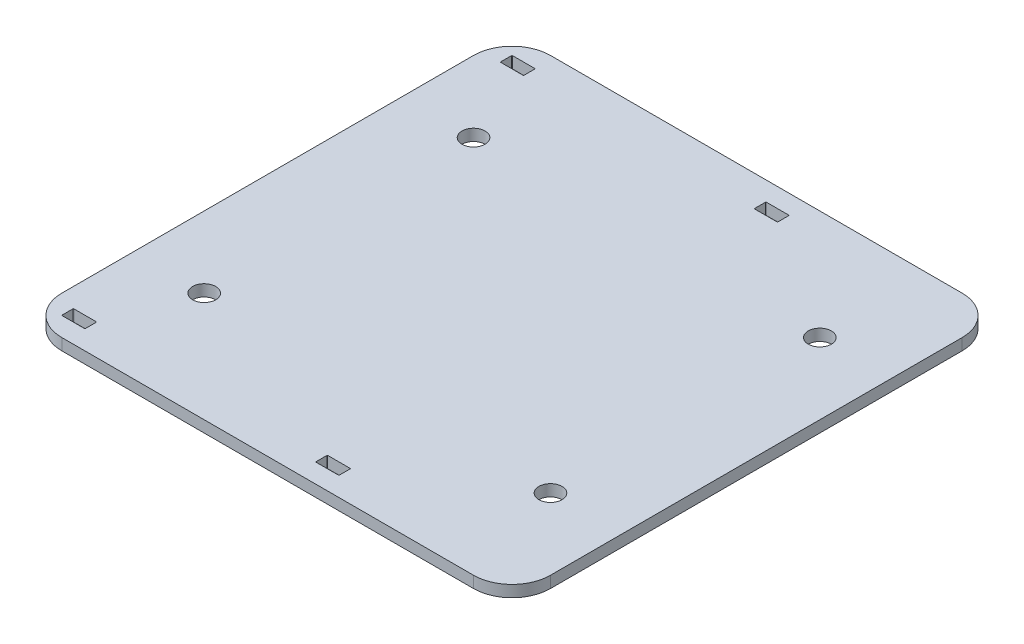
SolidWorks part; units mm, degrees
ref_plane "Front Plane" through (0, 0, 0) normal (0, 0, 1) x (1, 0, 0)
ref_plane "Top Plane" through (0, 0, 0) normal (0, 1, 0) x (1, 0, 0)
ref_plane "Right Plane" through (0, 0, 0) normal (1, 0, 0) x (0, 0, -1)
sketch "Sketch1" plane through (0, 0, 0) normal (0, 1, 0) x (1, 0, 0)
  line L0 (0, 63.5) -> (0, -63.5) construction
  line L1 (-53.5, 63.5) -> (53.5, 63.5)
  line L2 (-63.5, 53.5) -> (-63.5, -53.5)
  line L3 (-53.5, -63.5) -> (53.5, -63.5)
  line L4 (63.5, 53.5) -> (63.5, -53.5)
  line L5 (-63.5, 63.5) -> (63.5, -63.5) construction
  line L6 (-63.5, -63.5) -> (63.5, 63.5) construction
  line L7 (-63.5, 0) -> (63.5, 0) construction
  circle A0 centre (-45, 35) radius 3
  circle A1 centre (45, 35) radius 3
  circle A2 centre (45, -35) radius 3
  circle A3 centre (-45, -35) radius 3
  arc A4 (-63.5, -53.5) -> (-53.5, -63.5) centre (-53.5, -53.5) ccw
  arc A5 (53.5, -63.5) -> (63.5, -53.5) centre (53.5, -53.5) ccw
  arc A6 (53.5, 63.5) -> (63.5, 53.5) centre (53.5, 53.5) cw
  arc A7 (-53.5, 63.5) -> (-63.5, 53.5) centre (-53.5, 53.5) ccw
  point P0 (0, 0)
  dimension "D2" = 6
  dimension "D5" = 10
  dimension "D1" = 127
  dimension "D3" = 90
  dimension "D4" = 70
extrude "Boss-Extrude1" add sketch "Sketch1" along normal blind 3
sketch "Sketch2" plane through (0, 3, 0) normal (0, 1, 0) x (1, 0, 0)
  line L0 (-63.5, 53.5) -> (-63.5, -53.5) construction
  line L5 (13.5, -58.5) -> (7.5, -58.5)
  line L6 (13.5, -58.5) -> (13.5, -55.5)
  line L7 (13.5, -55.5) -> (7.5, -55.5)
  line L8 (7.5, -58.5) -> (7.5, -55.5)
  line L9 (-58.5, -58.5) -> (-52.5, -58.5)
  line L10 (-58.5, -58.5) -> (-58.5, -55.5)
  line L11 (-58.5, -55.5) -> (-52.5, -55.5)
  line L12 (-52.5, -58.5) -> (-52.5, -55.5)
  line L13 (-63.5, -53.5) -> (-63.5, -63.5) construction
  line L14 (-63.5, -63.5) -> (-53.5, -63.5) construction
  line L15 (-58.5, -58.5) -> (-58.5, -63.5) construction
  line L16 (-58.5, -58.5) -> (-63.5, -58.5) construction
  line L17 (-58.525, -55.475) -> (-52.475, -55.475)
  line L18 (-52.475, -58.525) -> (-52.475, -55.475)
  line L19 (-58.525, -58.525) -> (-52.475, -58.525)
  line L20 (-58.525, -58.525) -> (-58.525, -55.475)
  line L21 (13.525, -55.475) -> (7.475, -55.475)
  line L22 (7.475, -58.525) -> (7.475, -55.475)
  line L23 (13.525, -58.525) -> (7.475, -58.525)
  line L24 (13.525, -58.525) -> (13.525, -55.475)
  line L25 (-63.5, 0) -> (63.5, 0) construction
  line L26 (63.5, -53.5) -> (63.5, 53.5) construction
  line L27 (13.525, 58.525) -> (13.525, 55.475)
  line L28 (13.525, 55.475) -> (7.475, 55.475)
  line L29 (7.475, 58.525) -> (7.475, 55.475)
  line L30 (13.525, 58.525) -> (7.475, 58.525)
  line L31 (-58.525, 58.525) -> (-58.525, 55.475)
  line L32 (-58.525, 55.475) -> (-52.475, 55.475)
  line L33 (-52.475, 58.525) -> (-52.475, 55.475)
  line L34 (-58.525, 58.525) -> (-52.475, 58.525)
  dimension "D1" = 3
  dimension "D2" = 6
  dimension "D3" = 5
  dimension "D4" = 72
  dimension "D5" = 0.025
  dimension "D6" = 0.025
extrude "Cut-Extrude1" cut sketch "Sketch2" against normal up to next contours L32 L33 L34 L31 | L28 L29 L30 L27 | L19 L18 L17 L20 | L23 L22 L21 L24
fillet "Fillet1" radius 0.1 16 edges at (7.475, 1.5, -55.475) (-58.525, 1.5, -55.475) (-58.525, 1.5, 58.525) (7.475, 1.5, 58.525) (13.525, 1.5, -55.475) (-52.475, 1.5, -55.475) (-52.475, 1.5, 58.525) (13.525, 1.5, 58.525) (13.525, 1.5, 55.475) (-52.475, 1.5, 55.475) (13.525, 1.5, -58.525) (-52.475, 1.5, -58.525) (7.475, 1.5, 55.475) (-58.525, 1.5, 55.475) (7.475, 1.5, -58.525) (-58.525, 1.5, -58.525)
equation "\"TOLERANCE\"=0.025"
equation "\"D5@Sketch2\"=\"TOLERANCE\""
equation "\"D6@Sketch2\"=\"TOLERANCE\""
